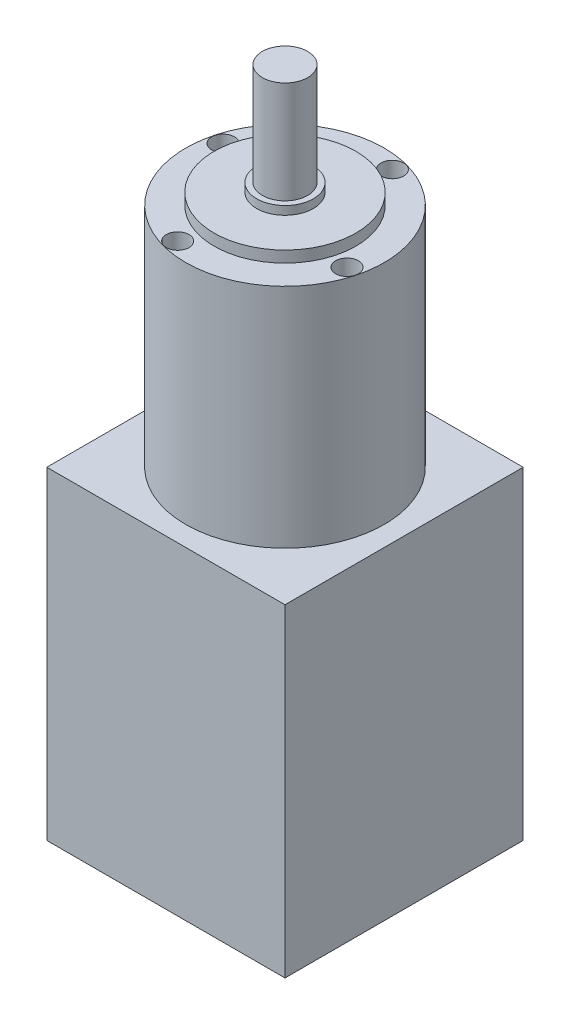
SolidWorks part; units mm, degrees
ref_plane "前视基准面" through (0, 0, 0) normal (0, 0, 1) x (1, 0, 0)
ref_plane "上视基准面" through (0, 0, 0) normal (0, 1, 0) x (1, 0, 0)
ref_plane "右视基准面" through (0, 0, 0) normal (1, 0, 0) x (0, 0, -1)
other "Configuration Table"
sketch "草图1" plane through (0, 0, 0) normal (0, 1, 0) x (1, 0, 0)
  line L1 (-21, -21) -> (21, -21)
  line L2 (-21, -21) -> (-21, 21)
  line L3 (-21, 21) -> (21, 21)
  line L4 (21, -21) -> (21, 21)
  line L5 (0, 21) -> (0, -21) construction
  line L6 (-21, 0) -> (21, 0) construction
  point P0 (0, 0)
  dimension "D1" = 42
extrude "凸台-拉伸1" add sketch "草图1" along normal blind 57
sketch "草图2" plane through (0, 0, 0) normal (0, 1, 0) x (1, 0, 0)
  circle A0 centre (0, 0) radius 17.5
  dimension "D1" = 35
extrude "凸台-拉伸2" add sketch "草图2" along normal blind 40 from surface at 57 starting at face at (0, 57, 0)
sketch "草图3" plane through (0, 0, 0) normal (0, 1, 0) x (1, 0, 0)
  circle A0 centre (0, 0) radius 12.5
  dimension "D1" = 25
extrude "凸台-拉伸3" add sketch "草图3" along normal blind 2 from surface at 97 starting at face at (0, 97, -17.5)
sketch "草图4" plane through (0, 0, 0) normal (0, 1, 0) x (1, 0, 0)
  circle A0 centre (0, 0) radius 5
  dimension "D1" = 10
extrude "凸台-拉伸4" add sketch "草图4" along normal blind 1.5 from surface at 99 starting at face at (0, 99, -12.5)
sketch "草图5" plane through (0, 0, 0) normal (0, 1, 0) x (1, 0, 0)
  circle A0 centre (0, 0) radius 4
  dimension "D1" = 8
extrude "凸台-拉伸5" add sketch "草图5" along normal blind 18 from surface at 100.5 starting at face at (0, 100.5, -5)
sketch "草图6" plane through (0, 0, 0) normal (0, 1, 0) x (1, 0, 0)
  line L0 (0, 0) -> (6.0578, 22.6081) construction
  line L1 (0, 37.4237) -> (0, -33.8342) construction
  circle A0 centre (0, 0) radius 17.45 construction
  circle A1 centre (3.9988, 14.9236) radius 2
  circle A2 centre (14.9236, -3.9988) radius 2
  circle A3 centre (-3.9988, -14.9236) radius 2
  circle A4 centre (-14.9236, 3.9988) radius 2
  point P14 (0, 0)
  dimension "D1" = 34.9
  dimension "D2" = 4
  dimension "D3" = 4
  dimension "D4" = 15
extrude "切除-拉伸2" cut sketch "草图6" against normal blind 15 from surface at 97 starting at face at (0, 97, -12.5)
